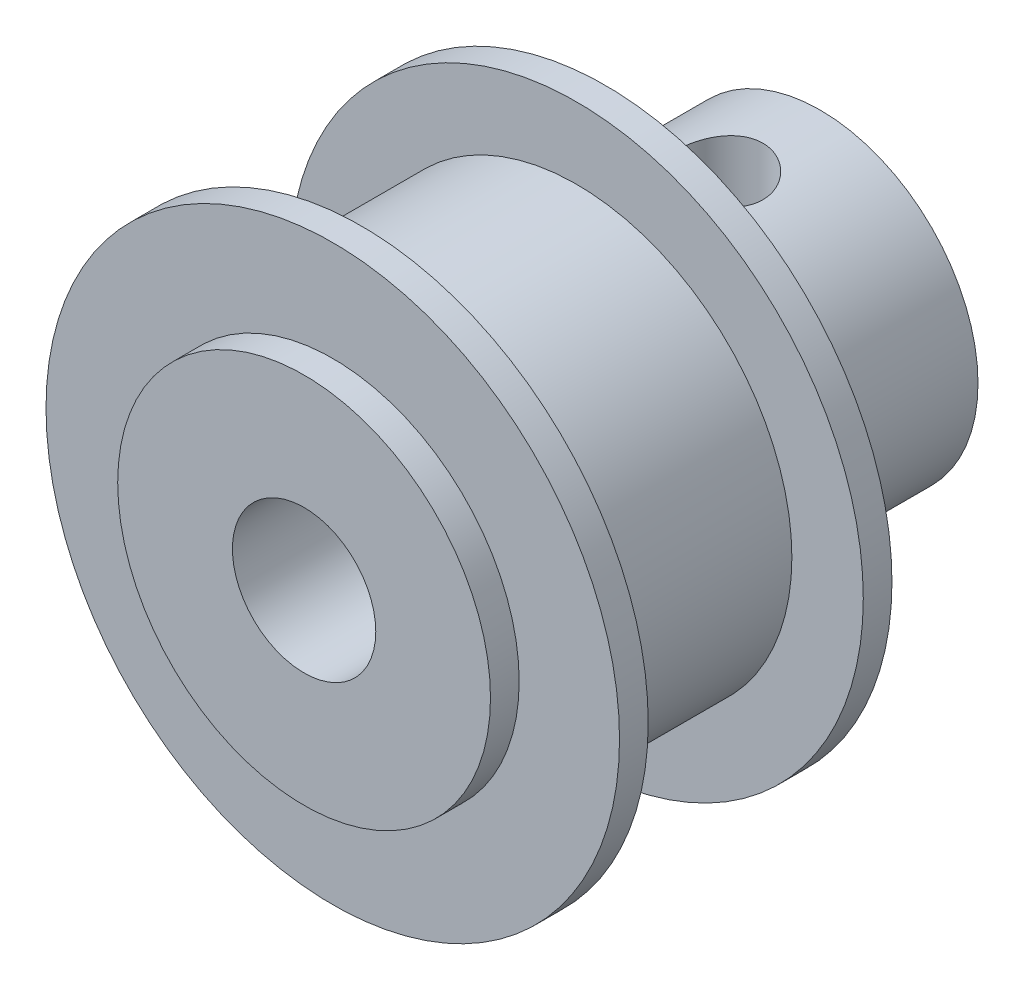
SolidWorks part; units mm, degrees
ref_plane "Front Plane" through (0, 0, 0) normal (0, 0, 1) x (1, 0, 0)
ref_plane "Top Plane" through (0, 0, 0) normal (0, 1, 0) x (1, 0, 0)
ref_plane "Right Plane" through (0, 0, 0) normal (1, 0, 0) x (0, 0, -1)
sketch "Sketch1" plane through (0, 0, 0) normal (0, 0, 1) x (1, 0, 0)
  circle A0 centre (0, 0) radius 5.5
extrude "Boss-Extrude1" add sketch "Sketch1" along normal blind 6.5
sketch "Sketch2" plane through (0, 0, 6.5) normal (0, 0, 1) x (1, 0, 0)
  circle A0 centre (0, 0) radius 6.5
extrude "Boss-Extrude2" add sketch "Sketch2" along normal blind 1
sketch "Sketch3" plane through (0, 0, 7.5) normal (0, 0, 1) x (1, 0, 0)
  circle A0 centre (0, 0) radius 10
extrude "Boss-Extrude3" add sketch "Sketch3" along normal blind 1
sketch "Sketch4" plane through (0, 0, 8.5) normal (0, 0, 1) x (1, 0, 0)
  circle A0 centre (0, 0) radius 7.51
extrude "Boss-Extrude4" add sketch "Sketch4" along normal blind 7.5
sketch "Sketch5" plane through (0, 0, 16) normal (0, 0, 1) x (1, 0, 0)
  circle A0 centre (0, 0) radius 10
extrude "Boss-Extrude5" add sketch "Sketch5" along normal blind 1
sketch "Sketch6" plane through (0, 0, 17) normal (0, 0, 1) x (1, 0, 0)
  circle A0 centre (0, 0) radius 6.5
extrude "Boss-Extrude6" add sketch "Sketch6" along normal blind 1
sketch "Sketch7" plane through (0, 0, 18) normal (0, 0, 1) x (1, 0, 0)
  circle A0 centre (0, 0) radius 2.5
extrude "Cut-Extrude1" cut sketch "Sketch7" against normal through all
hole_wizard "Ø3.0mm Dowel Hole1" positions "3DSketch2" profile "Sketch9" hole size "Ø3.0" standard "JIS"
sketch3d "3DSketch2"
  point P0 (0, 5.5, 3.5)
  point P1 (0, 0, 0)
sketch "Sketch9" plane through (0, 5.5, 3.5) normal (1, 0, 0) x (0, 0, 1)
  line L0 (0, 0) -> (0, 6.4013)
  line L1 (0, 6.4013) -> (1.5, 5.5)
  line L2 (1.5, 5.5) -> (1.5, 0)
  line L5 (1.5, 0) -> (0, 0)
  line L10 (0, 6.4013) -> (-1.5, 5.5) construction
  line L11 (0, -6.35) -> (0, 107.95) construction
  dimension "Hole Dia." = 3
  dimension "Hole Depth" = 5.5
  dimension "Drill Angle" = 118
